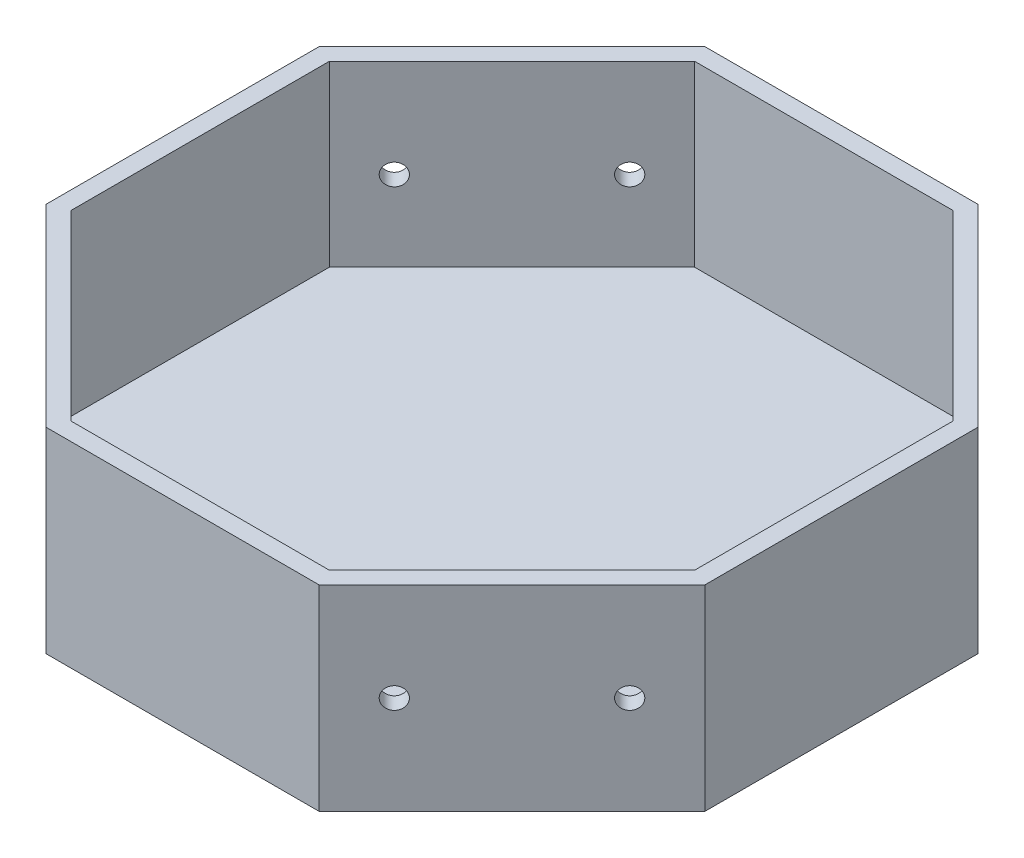
SolidWorks part; units mm, degrees
ref_plane "Plano frontal" through (0, 0, 0) normal (0, 0, 1) x (1, 0, 0)
ref_plane "Plano superior" through (0, 0, 0) normal (0, 1, 0) x (1, 0, 0)
ref_plane "Plano direito" through (0, 0, 0) normal (1, 0, 0) x (0, 0, -1)
sketch "Sketch1" plane through (0, 0, 0) normal (0, 1, 0) x (1, 0, 0)
  line L1 (55.4328, 22.961) -> (22.961, 55.4328)
  line L2 (22.961, 55.4328) -> (-22.961, 55.4328)
  line L3 (-22.961, 55.4328) -> (-55.4328, 22.961)
  line L4 (-55.4328, 22.961) -> (-55.4328, -22.961)
  line L5 (-55.4328, -22.961) -> (-22.961, -55.4328)
  line L6 (-22.961, -55.4328) -> (22.961, -55.4328)
  line L7 (22.961, -55.4328) -> (55.4328, -22.961)
  line L8 (55.4328, -22.961) -> (55.4328, 22.961)
  circle A0 centre (0, 0) radius 55.4328 construction
  dimension "D1" = 120
extrude "Boss-Extrude1" add sketch "Sketch1" along normal blind 3
sketch "Sketch2" plane through (0, 3, 0) normal (0, 1, 0) x (1, 0, 0)
  line L16 (52.4328, -21.7184) -> (52.4328, 21.7184)
  line L17 (52.4328, 21.7184) -> (21.7184, 52.4328)
  line L18 (21.7184, 52.4328) -> (-21.7184, 52.4328)
  line L19 (-21.7184, 52.4328) -> (-52.4328, 21.7184)
  line L20 (-52.4328, 21.7184) -> (-52.4328, -21.7184)
  line L21 (-52.4328, -21.7184) -> (-21.7184, -52.4328)
  line L22 (-21.7184, -52.4328) -> (21.7184, -52.4328)
  line L23 (21.7184, -52.4328) -> (52.4328, -21.7184)
  line L24 (52.4328, -21.7184) -> (52.4328, 21.7184)
  line L25 (52.4328, 21.7184) -> (21.7184, 52.4328)
  line L26 (21.7184, 52.4328) -> (-21.7184, 52.4328)
  line L27 (-21.7184, 52.4328) -> (-52.4328, 21.7184)
  line L28 (-52.4328, 21.7184) -> (-52.4328, -21.7184)
  line L29 (-52.4328, -21.7184) -> (-21.7184, -52.4328)
  line L30 (-21.7184, -52.4328) -> (21.7184, -52.4328)
  line L31 (21.7184, -52.4328) -> (52.4328, -21.7184)
  line L32 (55.4328, -22.961) -> (55.4328, 22.961)
  line L33 (55.4328, 22.961) -> (22.961, 55.4328)
  line L34 (22.961, 55.4328) -> (-22.961, 55.4328)
  line L35 (-22.961, 55.4328) -> (-55.4328, 22.961)
  line L36 (-55.4328, 22.961) -> (-55.4328, -22.961)
  line L37 (-55.4328, -22.961) -> (-22.961, -55.4328)
  line L38 (-22.961, -55.4328) -> (22.961, -55.4328)
  line L39 (22.961, -55.4328) -> (55.4328, -22.961)
  line L40 (55.4328, -22.961) -> (55.4328, 22.961)
  line L41 (55.4328, 22.961) -> (22.961, 55.4328)
  line L42 (22.961, 55.4328) -> (-22.961, 55.4328)
  line L43 (-22.961, 55.4328) -> (-55.4328, 22.961)
  line L44 (-55.4328, 22.961) -> (-55.4328, -22.961)
  line L45 (-55.4328, -22.961) -> (-22.961, -55.4328)
  line L46 (-22.961, -55.4328) -> (22.961, -55.4328)
  line L47 (22.961, -55.4328) -> (55.4328, -22.961)
  dimension "D1" = 3
  dimension "D2" = 0
extrude "Boss-Extrude2" add sketch "Sketch2" along normal blind 30
sketch "Sketch3" plane through (39.1969, 0, 39.1969) normal (0.7071, 0, 0.7071) x (0.7071, 0, -0.7071)
  line L0 (-22.961, 33) -> (22.961, 33) construction
  line L1 (-22.961, 33) -> (-22.961, 0) construction
  circle A0 centre (-14, 16.5) radius 1.8
  circle A1 centre (14, 16.5) radius 1.8
  point P4 (0, 0)
  point P7 (0, 33)
  point P10 (-22.961, 16.5)
  dimension "D1" = 3.6
  dimension "D2" = 3.6
  dimension "D3" = 14
  dimension "D4" = 14
extrude "Cut-Extrude1" cut sketch "Sketch3" against normal up to next
sketch "Sketch4" plane through (0, 0, 0) normal (0, 0, 1) x (1, 0, 0)
  line L0 (0, 0) -> (0, 54.8002) construction
pattern_circular "CirPattern1" count 4 every 90 about axis through (0, 0, 0) along (0, 1, 0) of "Cut-Extrude1"
equation "\"D2@Sketch3\"=\"D1@Sketch3\""
